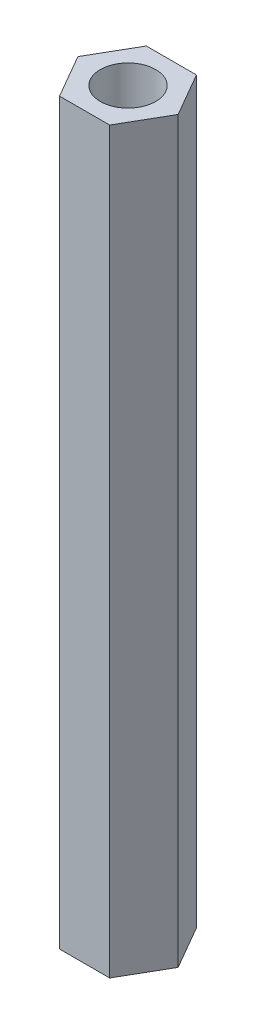
SolidWorks part; units mm, degrees
ref_plane "前视基准面" through (0, 0, 0) normal (0, 0, 1) x (1, 0, 0)
ref_plane "上视基准面" through (0, 0, 0) normal (0, 1, 0) x (1, 0, 0)
ref_plane "右视基准面" through (0, 0, 0) normal (1, 0, 0) x (0, 0, -1)
sketch "草图1" plane through (0, 0, 0) normal (0, 1, 0) x (1, 0, 0)
  line L1 (2.7135, 0) -> (1.3568, 2.35)
  line L2 (1.3568, 2.35) -> (-1.3568, 2.35)
  line L3 (-1.3568, 2.35) -> (-2.7135, 0)
  line L4 (-2.7135, 0) -> (-1.3568, -2.35)
  line L5 (-1.3568, -2.35) -> (1.3568, -2.35)
  line L6 (1.3568, -2.35) -> (2.7135, 0)
  circle A0 centre (0, 0) radius 2.35 construction
  circle A1 centre (0, 0) radius 1.5
extrude "凸台-拉伸1" add sketch "草图1" along normal blind 40
